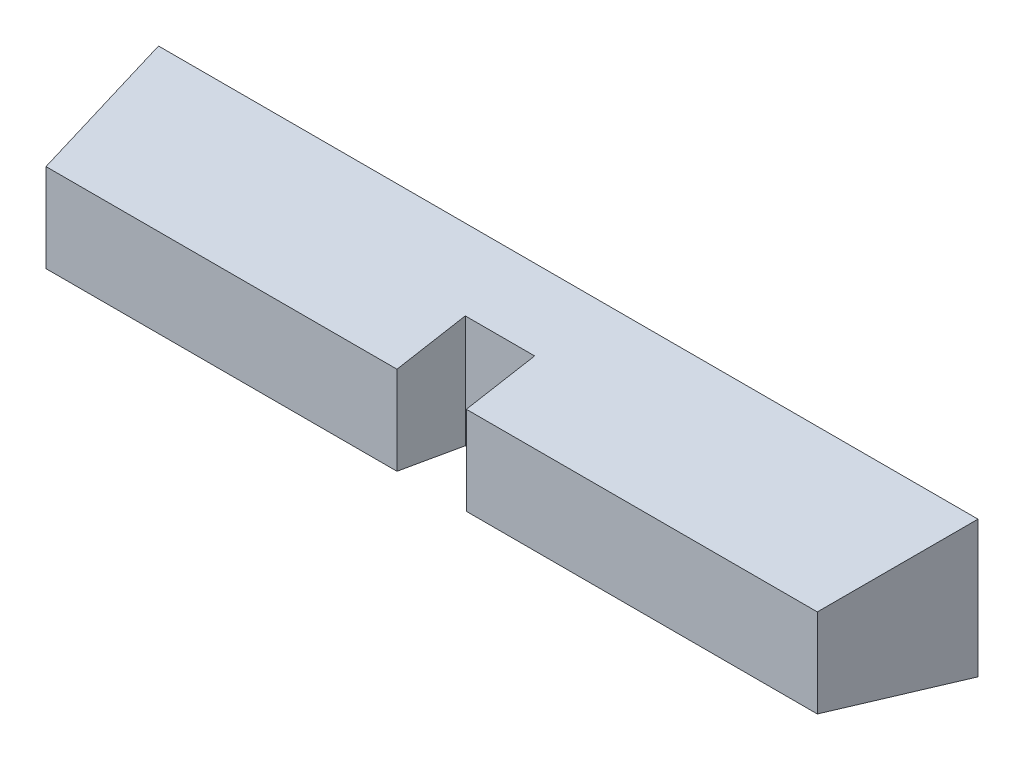
SolidWorks part; units mm, degrees
ref_plane "Front Plane" through (0, 0, 0) normal (1, 0, 0) x (0, 1, 0)
ref_plane "Top Plane" through (0, 0, 0) normal (0, 0, 1) x (0, 1, 0)
ref_plane "Right Plane" through (0, 0, 0) normal (0, 1, 0) x (-1, 0, 0)
sketch "Sketch1" plane through (0, 0, 0) normal (0, 0, 1) x (0, 1, 0)
  line L1 (-5, -30) -> (5, -30)
  line L2 (-5, -30) -> (-5, 30)
  line L3 (-5, 30) -> (5, 30)
  line L4 (5, -30) -> (5, 30)
  line L5 (-5, -30) -> (5, 30) construction
  line L6 (-5, 30) -> (5, -30) construction
  point P0 (0, 0)
  dimension "D1" = 10
  dimension "D2" = 60
extrude "Boss-Extrude1" add sketch "Sketch1" along normal blind 10 contours L3 L4 L1 L2
draft "Draft1" type of draft neutral plane draft angle 10 faces to draft 4 face at (-30, 0, 5) face at (0, -5, 5) face at (0, 5, 5) face at (30, 0, 5) neutral plane through (0, 0, 0) neutral plane normal (0, 0, -1) reverse direction yes parameters "D1"=10
sketch "Sketch2" plane through (0, 0, 10) normal (0, 0, 1) x (1, 0, 0)
  line L0 (0, 3.2367) -> (0, -3.2367) construction
  line L4 (-2.54, -15) -> (2.54, -15)
  line L5 (-2.54, -15) -> (-2.54, 15)
  line L6 (-2.54, 15) -> (2.54, 15)
  line L7 (2.54, -15) -> (2.54, 15)
  line L8 (-2.54, -15) -> (2.54, 15) construction
  line L9 (-2.54, 15) -> (2.54, -15) construction
  point P6 (0, 0)
  dimension "D1" = 5.08
  dimension "D2" = 30
extrude "Cut-Extrude1" cut sketch "Sketch2" against normal blind 5 contours L6 L7 L4 L5
